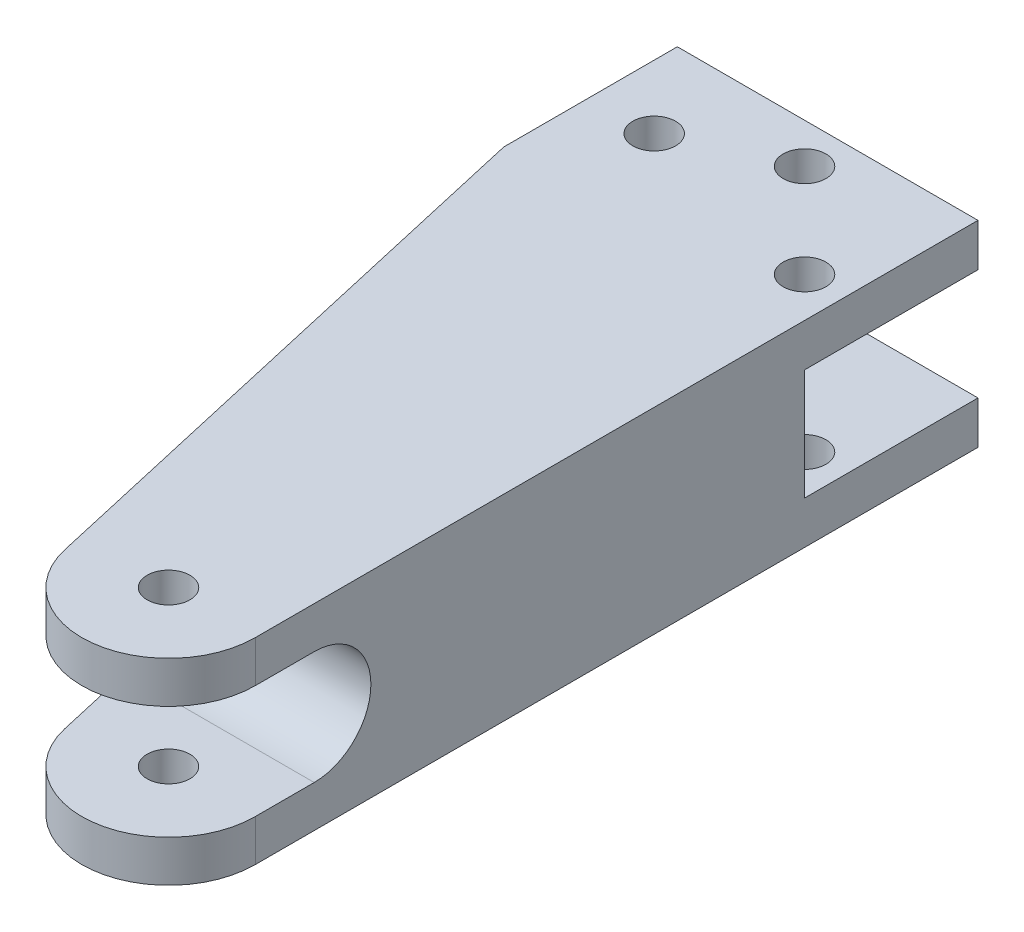
SolidWorks part; units mm, degrees
material "2024-T3"
ref_plane "Front Plane" through (0, 0, 0) normal (0, 0, 1) x (1, 0, 0)
ref_plane "Top Plane" through (0, 0, 0) normal (0, 1, 0) x (1, 0, 0)
ref_plane "Right Plane" through (0, 0, 0) normal (1, 0, 0) x (0, 0, -1)
sketch "Sketch1" plane through (0, 0, 0) normal (0, 0, 1) x (1, 0, 0)
  line L0 (-9.525, -10.795) -> (9.525, -10.795)
  line L1 (-9.525, -10.795) -> (-9.525, 10.795)
  line L2 (9.525, -10.795) -> (9.525, 10.795)
  line L3 (-9.525, 10.795) -> (9.525, 10.795)
  line L4 (-9.525, -10.795) -> (9.525, 10.795) construction
  line L5 (9.525, -10.795) -> (-9.525, 10.795) construction
  point P1 (0, 0)
  dimension "D1" = 21.59
  dimension "D2" = 19.05
extrude "Boss-Extrude1" add sketch "Sketch1" along normal blind 88.9
sketch "Sketch3" plane through (0, 10.795, 0) normal (0, 1, 0) x (1, 0, 0)
  line L0 (-9.525, -88.9) -> (-9.525, 0) construction
  line L1 (9.525, -88.9) -> (9.525, 0) construction
  line L2 (9.525, -88.9) -> (-9.525, -88.9) construction
  arc A0 (-9.525, -79.375) -> (9.525, -79.375) centre (0, -79.375) ccw
extrude "Cut-Extrude-Thin1" cut sketch "Sketch3" against normal blind 88.9 and the other way through all thin
sketch "Sketch4" plane through (0, 10.795, 0) normal (0, 1, 0) x (1, 0, 0)
  line L0 (5.1435, -14.6685) -> (9.525, -14.6685) construction
  line L1 (9.525, -79.375) -> (9.525, 0) construction
  line L2 (-9.525, 0) -> (9.525, -19.05) construction
  line L3 (-5.1435, -4.3815) -> (-5.1435, 0) construction
  line L4 (-9.525, 0) -> (9.525, 0) construction
  line L5 (-9.525, 0) -> (-9.525, -19.05) construction
  line L6 (-9.525, -19.05) -> (9.525, -19.05) construction
  line L7 (9.525, 0) -> (9.525, -19.05) construction
  circle A0 centre (0, -79.375) radius 2.3495
  circle A1 centre (5.1435, -14.6685) radius 2.3495
  circle A2 centre (-5.1435, -4.3815) radius 2.3495
  dimension "D1" = 4.699
  dimension "D2" = 4.3815
  dimension "D3" = 4.3815
extrude "Cut-Extrude1" cut sketch "Sketch4" against normal through all
sketch "Sketch5" plane through (0, 10.795, 0) normal (0, 1, 0) x (1, 0, 0)
  line L0 (-9.525, 0) -> (-23.495, 0)
  line L1 (-23.495, 0) -> (-23.495, -19.05)
  line L2 (-9.525, -79.375) -> (-9.525, 0) construction
  line L3 (-9.525, -79.375) -> (-9.525, 0)
  line L4 (-23.495, -19.05) -> (-9.2876, -81.4883)
  arc A0 (-9.525, -79.375) -> (9.525, -79.375) centre (0, -79.375) ccw construction
  arc A1 (-9.525, -79.375) -> (9.525, -79.375) centre (0, -79.375) ccw
  circle A2 centre (-16.51, -9.525) radius 2.3495
  circle A3 centre (-5.1435, -4.3815) radius 2.3495 construction
  point P14 (-16.51, 0)
  point P17 (-23.495, -9.525)
  line M9 (-9.525, 0) -> (-9.525, -79.375)
  arc M10 (-9.525, -79.375) -> (9.525, -79.375) centre (0, -79.375) ccw
  dimension "D1" = 13.97
  dimension "D2" = 19.05
  dimension "D3" = 12.819
extrude "Boss-Extrude2" add sketch "Sketch5" against normal up to surface (21.59 mm away) contours L1 L4 L0 A2 M10 M9 up to face at (0, -10.795, 81.7245)
sketch "Sketch6" plane through (9.525, 0, 0) normal (1, 0, 0) x (0, 0, -1)
  line L0 (19.05, -6.096) -> (19.05, 6.096)
  line L1 (19.05, -6.096) -> (-19.05, -6.096)
  line L2 (19.05, 6.096) -> (-19.05, 6.096)
  line L3 (-19.05, -6.096) -> (-19.05, 6.096)
  line L4 (19.05, -6.096) -> (-19.05, 6.096) construction
  line L5 (19.05, 6.096) -> (-19.05, -6.096) construction
  line L6 (-92.075, -6.223) -> (-72.898, -6.223)
  line L7 (-92.075, -6.223) -> (-92.075, 6.223)
  line L9 (-92.075, 6.223) -> (-72.898, 6.223)
  line L10 (-92.075, -6.223) -> (-69.1843, 4.9934) construction
  line L11 (-69.1843, -4.9934) -> (-92.075, 6.223) construction
  line L12 (-79.375, -10.795) -> (-79.375, 10.795) construction
  line L13 (-79.375, -10.795) -> (-79.375, 10.795) construction
  arc A0 (-72.898, 6.223) -> (-72.898, -6.223) centre (-72.898, 0) cw
  point P1 (0, 0)
  point P2 (-79.375, 0)
  point P14 (-79.375, 0)
  dimension "D1" = 12.192
  dimension "D2" = 19.05
extrude "Cut-Extrude2" cut sketch "Sketch6" against normal through all
